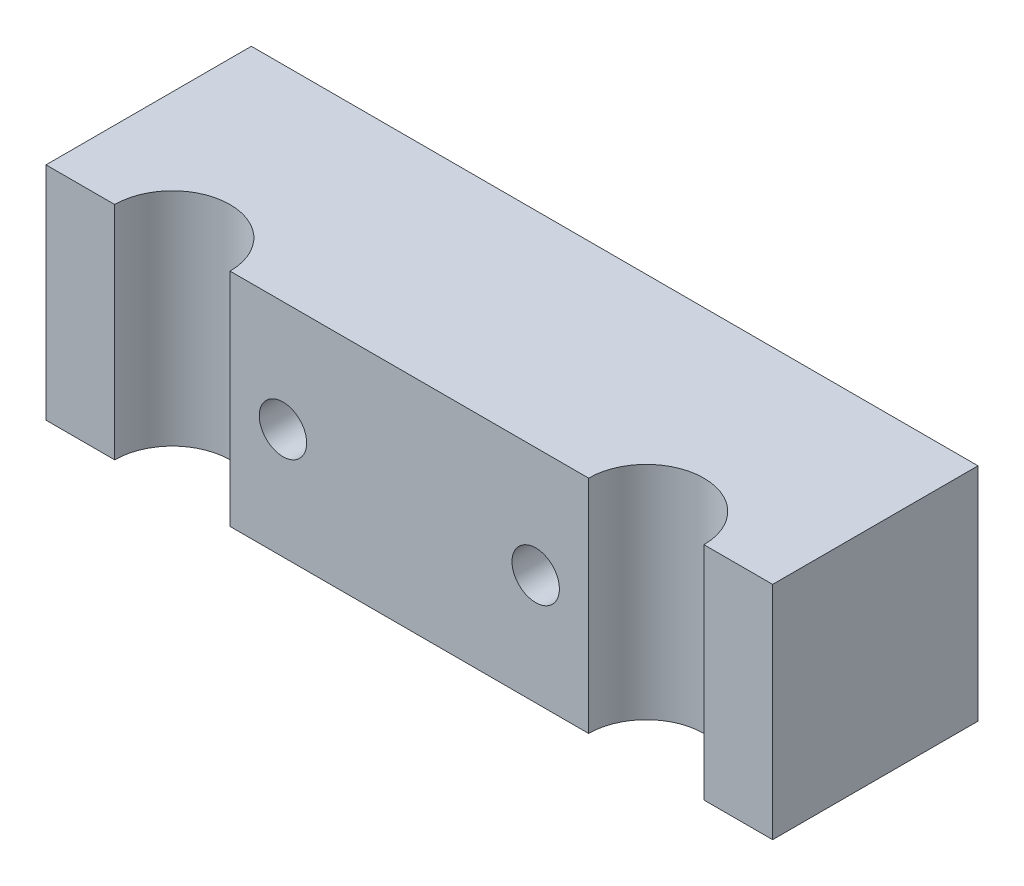
SolidWorks part; units mm, degrees
material "ABS"
ref_plane "Front" through (0, 0, 0) normal (0, 0, 1) x (1, 0, 0)
ref_plane "Top" through (0, 0, 0) normal (0, 1, 0) x (1, 0, 0)
ref_plane "Right" through (0, 0, 0) normal (1, 0, 0) x (0, 0, -1)
sketch "Эскиз1" plane through (0, 0, 0) normal (0, 0, 1) x (1, 0, 0)
  line L1 (-23, -7) -> (23, -7)
  line L2 (-23, -7) -> (-23, 7)
  line L3 (-23, 7) -> (23, 7)
  line L4 (23, -7) -> (23, 7)
  line L5 (-23, -7) -> (23, 7) construction
  line L6 (-23, 7) -> (23, -7) construction
  point P0 (0, 0)
  dimension "D1" = 46
  dimension "D2" = 14
extrude "Бобышка-Вытянуть1" add sketch "Эскиз1" along normal blind 13
sketch "Эскиз2" plane through (0, 0, 13) normal (0, 0, 1) x (1, 0, 0)
  line L0 (-23, 0) -> (23, 0) construction
  line L1 (-23, 7) -> (-23, -7) construction
  line L2 (23, -7) -> (23, 7) construction
  line L3 (0, 7) -> (0, 0) construction
  line L4 (23, 7) -> (-23, 7) construction
  circle A0 centre (-8, 0) radius 1.5
  circle A1 centre (8, 0) radius 1.5
  dimension "D1" = 8
extrude "Вырез-Вытянуть1" cut sketch "Эскиз2" against normal up to next
sketch "Эскиз3" plane through (0, 7, 0) normal (0, 1, 0) x (1, 0, 0)
  line L0 (0, 0) -> (0, -13) construction
  line L1 (23, 0) -> (-23, 0) construction
  line L2 (23, -13) -> (-23, -13) construction
  line L3 (0, -13) -> (-15, -13) construction
  circle A0 centre (-15, -13) radius 3.65
  circle A1 centre (15, -13) radius 3.65
  dimension "D2" = 7.3
  dimension "D3" = 13
  dimension "D1" = 15
extrude "Вырез-Вытянуть2" cut sketch "Эскиз3" against normal up to next
sketch "Эскиз4" plane through (0, 0, 0) normal (0, 0, -1) x (-1, 0, 0)
  circle A0 centre (-8, 0) radius 3
  circle A1 centre (8, 0) radius 3
extrude "Вырез-Вытянуть3" cut sketch "Эскиз4" against normal blind 3.8
